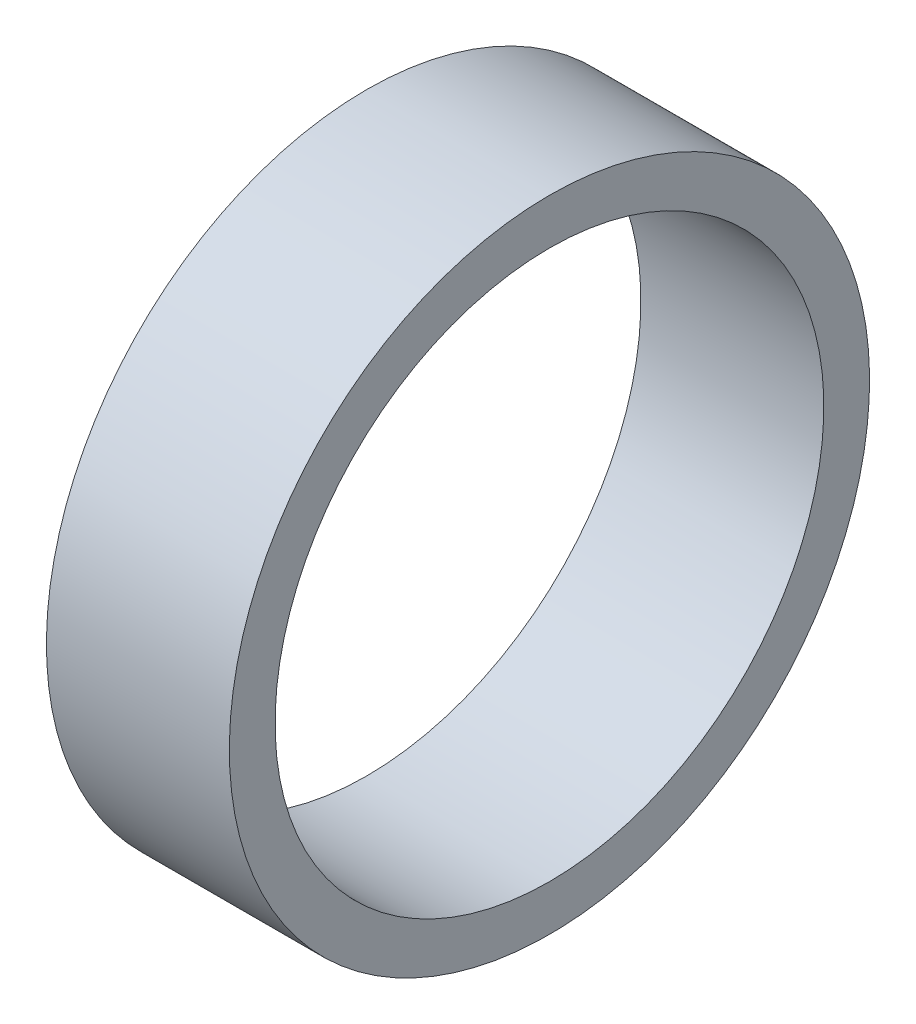
SolidWorks part; units mm, degrees
ref_plane "Front Plane" through (0, 0, 0) normal (0, 0, 1) x (1, 0, 0)
ref_plane "Top Plane" through (0, 0, 0) normal (0, 1, 0) x (1, 0, 0)
ref_plane "Right Plane" through (0, 0, 0) normal (1, 0, 0) x (0, 0, -1)
sketch "Sketch1" plane through (0, 0, 0) normal (0, 0, 1) x (1, 0, 0)
  line L0 (0, 0) -> (2000, 0) construction
  line L1 (1100, 120) -> (1100, 140)
  line L2 (1100, 140) -> (1180, 140)
  line L3 (1180, 140) -> (1180, 120)
  line L4 (1180, 120) -> (1100, 120)
revolve "Revolve1" add sketch "Sketch1" angle 360 about L0
